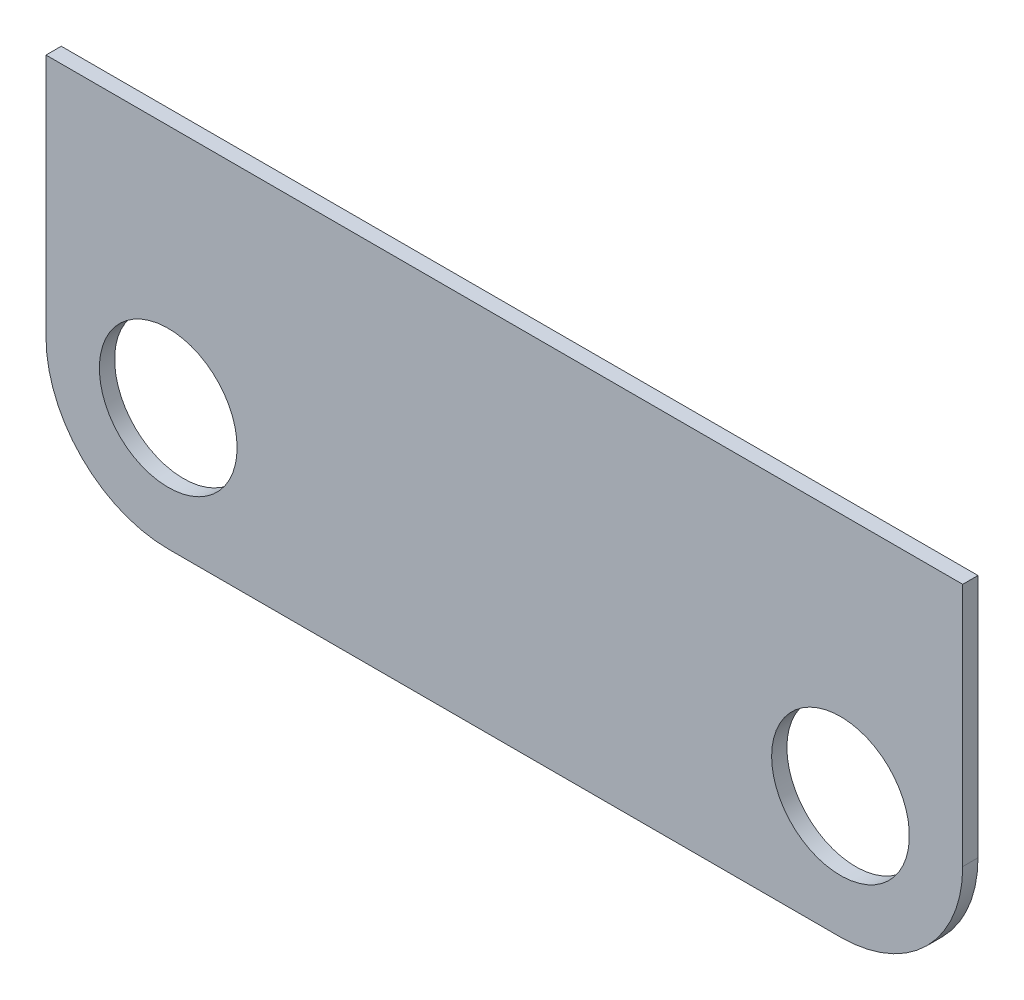
SolidWorks part; units mm, degrees
material "6061 Alloy"
ref_plane "Front Plane" through (0, 0, 0) normal (0, 0, 1) x (1, 0, 0)
ref_plane "Top Plane" through (0, 0, 0) normal (0, 1, 0) x (1, 0, 0)
ref_plane "Right Plane" through (0, 0, 0) normal (1, 0, 0) x (0, 0, -1)
sketch "Sketch1" plane through (0, 0, 0) normal (0, 0, 1) x (1, 0, 0)
  line L0 (0, 0) -> (0, 38.1) construction
  line L1 (69.85, -38.1) -> (-69.85, -38.1)
  line L2 (95.25, -12.7) -> (95.25, 38.1)
  line L3 (95.25, 38.1) -> (-95.25, 38.1)
  line L4 (-95.25, -12.7) -> (-95.25, 38.1)
  line L5 (95.25, -38.1) -> (-95.25, 38.1) construction
  line L6 (95.25, 38.1) -> (-95.25, -38.1) construction
  arc A0 (69.85, -38.1) -> (95.25, -12.7) centre (69.85, -12.7) ccw
  arc A1 (-69.85, -38.1) -> (-95.25, -12.7) centre (-69.85, -12.7) cw
  circle A2 centre (-69.85, -12.7) radius 14.3129
  circle A3 centre (69.85, -12.7) radius 14.3129
  point P0 (0, 0)
  dimension "D3" = 25.4
  dimension "D4" = 28.6258
  dimension "D1" = 190.5
  dimension "D2" = 76.2
extrude "Boss-Extrude1" add sketch "Sketch1" along normal blind 3.175
